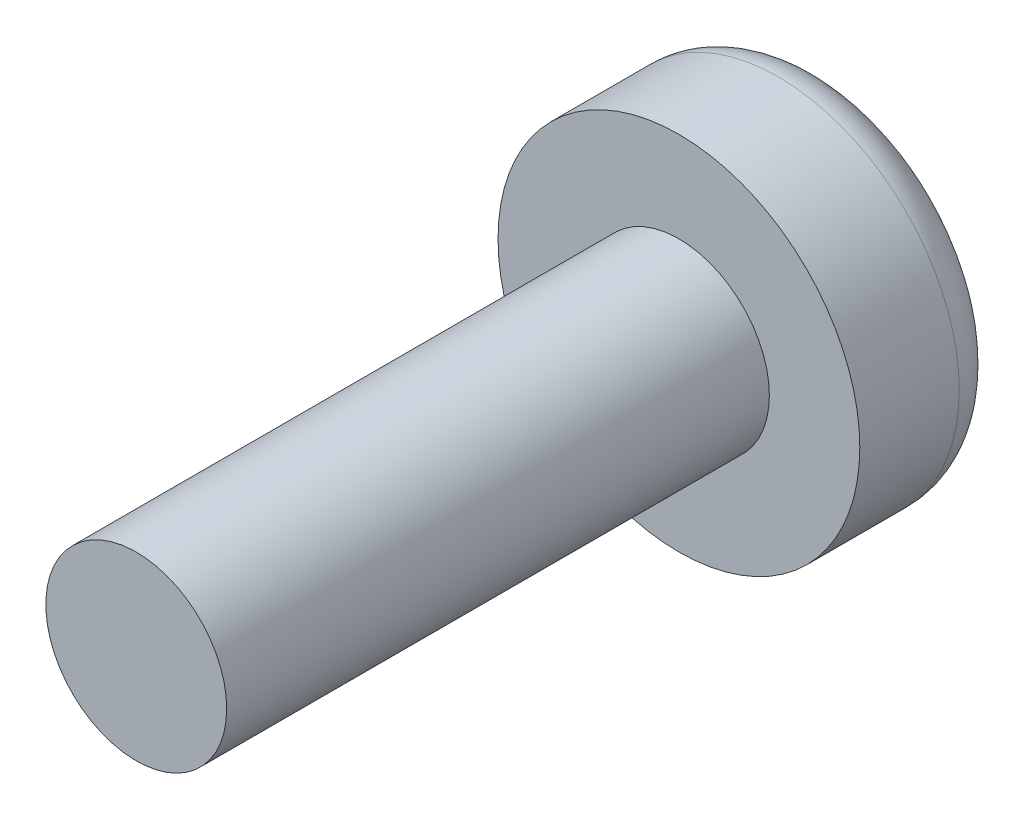
SolidWorks part; units mm, degrees
ref_plane "Plan de face" through (0, 0, 0) normal (0, 0, 1) x (1, 0, 0)
ref_plane "Plan de dessus" through (0, 0, 0) normal (0, 1, 0) x (1, 0, 0)
ref_plane "Plan de droite" through (0, 0, 0) normal (1, 0, 0) x (0, 0, -1)
sketch "Esquisse1" plane through (0, 0, 0) normal (0, 0, 1) x (1, 0, 0)
  line L0 (0, 14.3524) -> (0, -13.0189) construction
  line L1 (-0.258, 1.3181) -> (0.258, 1.3181)
  line L2 (0.258, 1.3181) -> (0.258, 0.258)
  line L3 (-1.2952, 0) -> (1.0066, 0) construction
  line L4 (0.258, 0.258) -> (1.224, 0.258)
  line L5 (1.224, 0.258) -> (1.224, -0.258)
  line L6 (-1.224, 0.258) -> (-1.224, -0.258)
  line L7 (-0.258, 0.258) -> (-1.224, 0.258)
  line L8 (-0.258, 1.3181) -> (-0.258, 0.258)
  line L9 (-0.258, -1.3181) -> (-0.258, -0.258)
  line L10 (0.258, -1.3181) -> (0.258, -0.258)
  line L11 (-0.258, -1.3181) -> (0.258, -1.3181)
  line L12 (0.258, -0.258) -> (1.224, -0.258)
  line L13 (-0.258, -0.258) -> (-1.224, -0.258)
  circle A0 centre (0, 0) radius 2.4
  circle A1 centre (0, 0) radius 2.1651
  point P17 (0, 1.3181)
  point P22 (1.224, 0)
  point P23 (-1.224, 0)
  dimension "D4" = 4.8
  dimension "D1" = 2.448
  dimension "D2" = 0.516
  dimension "D3" = 0.516
extrude "Boss.-Extru.1" add sketch "Esquisse1" along normal blind 1.92 contours A0 A1 | A1 L9 L13 L6 L7 L8 L1 L2 L4 L5 L12 L10 L11 | L13 L9 L11 L10 L12 L5 L4 L2 L1 L8 L7 L6
sketch "Esquisse2" plane through (0, 0, 0) normal (0, 0, -1) x (-1, 0, 0)
  line L0 (0, 3.0361) -> (0, -3.1723)
  line L1 (-2.7183, 0) -> (3.0972, 0) construction
  line L2 (-0.258, 1.224) -> (0.258, 1.224)
  line L3 (0.258, 1.224) -> (0.258, 0.258)
  line L4 (0.258, 0.258) -> (1.224, 0.258)
  line L5 (1.224, 0.258) -> (1.224, -0.258)
  line L6 (-1.224, 0.258) -> (-1.224, -0.258)
  line L7 (-0.258, 0.258) -> (-1.224, 0.258)
  line L8 (-0.258, 1.224) -> (-0.258, 0.258)
  line L9 (0.258, -0.258) -> (1.224, -0.258)
  line L10 (0.258, -1.224) -> (0.258, -0.258)
  line L11 (-0.258, -1.224) -> (0.258, -1.224)
  line L12 (-0.258, -1.224) -> (-0.258, -0.258)
  line L13 (-0.258, -0.258) -> (-1.224, -0.258)
  point P14 (0, 1.224)
  point P15 (1.224, 0)
  point P20 (-1.224, 0)
  dimension "D1" = 2.448
  dimension "D2" = 2.448
  dimension "D3" = 0.516
  dimension "D4" = 0.516
extrude "Enlèv. mat.-Extru.1" cut sketch "Esquisse2" against normal blind 0.72 contours L1 L6 L13 L12 L11 L0 | L6 L1 L0 L2 L8 L7 | L0 L1 L5 L4 L3 L2 | L1 L0 L11 L10 L9 L5
fillet "Congé6" radius 0.36 4 edges at (1.224, 0, 0.72) (-1.224, 0, 0.72) (0, -1.224, 0.72) (0, 1.224, 0.72)
sketch "Esquisse3" plane through (0, 0, 1.92) normal (0, 0, 1) x (1, 0, 0)
  line L0 (0, 2.5155) -> (0, -2.7683) construction
  circle A0 centre (0, 0) radius 1.2
  dimension "D1" = 2.4
extrude "Boss.-Extru.2" add sketch "Esquisse3" along normal blind 7.2
fillet "Congé7" radius 0.6 1 edges at (2.4, 0, 0)
